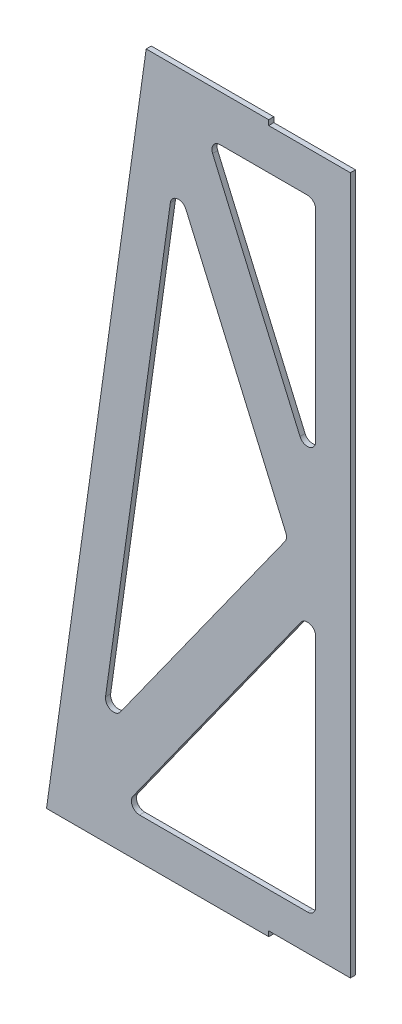
SolidWorks part; units mm, degrees
material "Balsa"
ref_plane "Front Plane" through (0, 0, 0) normal (0, 0, 1) x (1, 0, 0)
ref_plane "Top Plane" through (0, 0, 0) normal (0, 1, 0) x (1, 0, 0)
ref_plane "Right Plane" through (0, 0, 0) normal (1, 0, 0) x (0, 0, -1)
sketch "Sketch1" plane through (0, 0, 0) normal (0, 0, 1) x (1, 0, 0)
  line L1 (65.0875, 0) -> (65.0875, -233.68)
  line L2 (65.0875, -233.68) -> (-57.023, -233.68)
  line L3 (-57.023, -233.68) -> (0, 0)
  line L4 (0, 0) -> (0, 1.5875)
  line L9 (0, 1.5875) -> (38.1, 1.5875)
  line L10 (38.1, 1.5875) -> (38.1, 0)
  line L11 (38.1, 0) -> (65.0875, 0)
  dimension "D1" = 65.0875
  dimension "D2" = 233.68
  dimension "D3" = 122.1105
  dimension "D4" = 38.1
  dimension "D5" = 1.5875
extrude "Boss-Extrude1" [suppressed] add sketch "Sketch1" along normal blind 1.5875
sketch "Sketch2" [suppressed] plane through (0, 0, 1.5875) normal (0, 0, 1) x (1, 0, 0)
  line L0 (10.0135, -12.7) -> (-40.8513, -220.98)
  line L1 (-15.4189, -116.84) -> (52.3875, -12.7) construction
  line L2 (-15.4189, -116.84) -> (52.3875, -220.98) construction
  line L3 (-40.8513, -220.98) -> (52.3875, -116.84) construction
  line L4 (52.3875, -116.84) -> (10.0135, -12.7) construction
  line L5 (-35.1742, -226.0628) -> (61.2394, -118.3768)
  line L6 (61.2394, -118.3768) -> (17.0716, -9.8281)
  line L8 (10.0135, -12.7) -> (52.3875, -12.7)
  line L9 (-24.5118, -116.84) -> (46.0018, -8.5422)
  line L10 (-24.5118, -116.84) -> (46.0018, -225.1378)
  line L11 (-46.5284, -215.8972) -> (43.5356, -115.3032)
  line L12 (43.5356, -115.3032) -> (2.9554, -15.5719)
  line L13 (-6.326, -116.84) -> (58.7732, -16.8578)
  line L14 (10.361, -11.1125) -> (-40.8513, -220.98)
  line L15 (-40.8513, -220.98) -> (52.3875, -220.98)
  line L16 (52.3875, -220.98) -> (52.3875, -12.7)
  line L17 (52.3875, -12.7) -> (25.4, -12.7)
  line L18 (25.4, -12.7) -> (25.4, -11.1125)
  line L19 (25.4, -11.1125) -> (10.361, -11.1125)
  line L21 (-40.8513, -220.98) -> (52.3875, -220.98)
  line L22 (52.3875, -220.98) -> (52.3875, -12.7)
  line L23 (-6.326, -116.84) -> (58.7732, -216.8222)
  dimension "D2" = 214.401
  dimension "D3" = 7.62
  dimension "D4" = 7.62
  dimension "D1" = 12.7
extrude "Cut-Extrude1" [suppressed] cut sketch "Sketch2" against normal blind 2.54 contours L6 L9 L8 | L6 L22 L13 | L13 L23 L11 L12 | L9 L12 L0 | L5 L23 L22 | L5 L21 L10 | L0 L11 L10
fillet "Fillet3" [suppressed] radius 2.54
sketch "Sketch3" [suppressed] plane through (0, 0, 0) normal (0, 0, -1) x (-1, 0, 0)
  line L0 (-38.1, 0) -> (-38.1, -233.68) construction
  line L1 (57.023, -233.68) -> (-65.0875, -233.68) construction
  line L3 (-65.0875, -233.68) -> (-65.0875, 0) construction
  line L4 (-38.1, -233.68) -> (-65.0875, -233.68)
  line L5 (-38.1, -233.68) -> (-38.1, -232.0925)
  line L6 (-38.1, -232.0925) -> (-65.0875, -232.0925)
  line L7 (-65.0875, -233.68) -> (-65.0875, -232.0925)
  dimension "D1" = 1.5875
extrude "Cut-Extrude2" [suppressed] cut sketch "Sketch3" against normal blind 2.54
sketch "Sketch4" [suppressed] plane through (0, 0, 1.5875) normal (0, 0, 1) x (1, 0, 0)
  line L0 (1.8159, 1.5875) -> (-56.5165, -233.68)
  line L1 (38.1, 1.5875) -> (0, 1.5875) construction
  line L2 (-57.023, -233.68) -> (38.1, -233.68) construction
  line L3 (-56.5165, -233.68) -> (-57.023, -233.68)
  line L4 (-57.023, -233.68) -> (0, 0)
  line L5 (0, 0) -> (0, 1.5875)
  line L6 (0, 1.5875) -> (1.8159, 1.5875)
extrude "Cut-Extrude3" [suppressed] cut sketch "Sketch4" against normal up to next
sketch "Sketch6" plane through (0, 0, 0) normal (0, 0, 1) x (1, 0, 0)
  line L1 (63.5, 12.998) -> (63.5, -205.442)
  line L2 (63.5, -205.442) -> (-30.988, -205.442)
  line L5 (0, 14.5855) -> (38.1, 14.5855)
  line L6 (38.1, 14.5855) -> (38.1, 12.998)
  line L7 (38.1, 12.998) -> (63.5, 12.998)
  line L8 (-30.988, -205.442) -> (0, 14.5855)
  dimension "D1" = 63.5
  dimension "D2" = 94.488
  dimension "D3" = 218.44
  dimension "D4" = 38.1
  dimension "D5" = 1.5875
extrude "Boss-Extrude2" add sketch "Sketch6" along normal blind 1.5875
sketch "Sketch7" plane through (0, 0, 1.5875) normal (0, 0, 1) x (1, 0, 0)
  line L0 (10.8131, 0.298) -> (52.6982, 0.298) construction
  line L1 (52.6982, 0.298) -> (52.6982, -192.742) construction
  line L2 (52.6982, -192.742) -> (-16.374, -192.742) construction
  line L3 (-16.374, -192.742) -> (10.8131, 0.298) construction
  line L5 (63.5, -205.442) -> (63.5, 12.998) construction
  line L6 (-30.988, -205.442) -> (63.5, -205.442) construction
  line L8 (-16.374, -192.742) -> (52.6982, -96.222) construction
  line L9 (52.6982, -96.222) -> (10.8131, 0.298) construction
  line L10 (-14.0781, -176.4401) -> (43.9901, -95.2968)
  line L11 (43.9901, -95.2968) -> (8.7778, -14.1535)
  line L12 (-7.0039, -192.742) -> (52.6982, -109.3157)
  line L13 (52.6982, -77.0804) -> (19.1197, 0.298)
  line L14 (19.1197, 0.298) -> (52.6982, 0.298)
  line L15 (52.6982, 0.298) -> (52.6982, -77.0804)
  line L16 (8.7778, -14.1535) -> (-14.0781, -176.4401)
  line L17 (-7.0039, -192.742) -> (52.6982, -192.742)
  line L18 (52.6982, -192.742) -> (52.6982, -109.3157)
  line L19 (63.5, 12.998) -> (38.1, 12.998) construction
  line L20 (0, 14.5855) -> (-30.988, -205.442) construction
  dimension "D2" = 10.8018
  dimension "D3" = 12.7
  dimension "D4" = 12.7
  dimension "D5" = 7.62
  dimension "D6" = 7.62
  dimension "D7" = 7.62
  dimension "D8" = 7.62
  dimension "D9" = 7.62
  dimension "D10" = 7.62
  dimension "D11" = 7.62
  dimension "D12" = 7.62
  dimension "D13" = 12.7
extrude "Cut-Extrude4" cut sketch "Sketch7" against normal through all
fillet "Fillet4" radius 2.54 9 edges at (8.7778, -14.1535, 0.7937) (19.1197, 0.298, 0.7937) (52.6982, 0.298, 0.7937) (52.6982, -77.0804, 0.7937) (43.9901, -95.2968, 0.7937) (52.6982, -109.3157, 0.7937) (52.6982, -192.742, 0.7937) (-7.0039, -192.742, 0.7937) (-14.0781, -176.4401, 0.7937)
sketch "Sketch8" plane through (0, 0, 1.5875) normal (0, 0, 1) x (1, 0, 0)
  line L1 (63.5, -205.442) -> (38.1, -205.442)
  line L2 (63.5, -205.442) -> (63.5, -203.8545)
  line L3 (63.5, -203.8545) -> (38.1, -203.8545)
  line L4 (38.1, -205.442) -> (38.1, -203.8545)
  dimension "D1" = 1.5875
  dimension "D2" = 25.4
extrude "Cut-Extrude5" cut sketch "Sketch8" against normal through all
